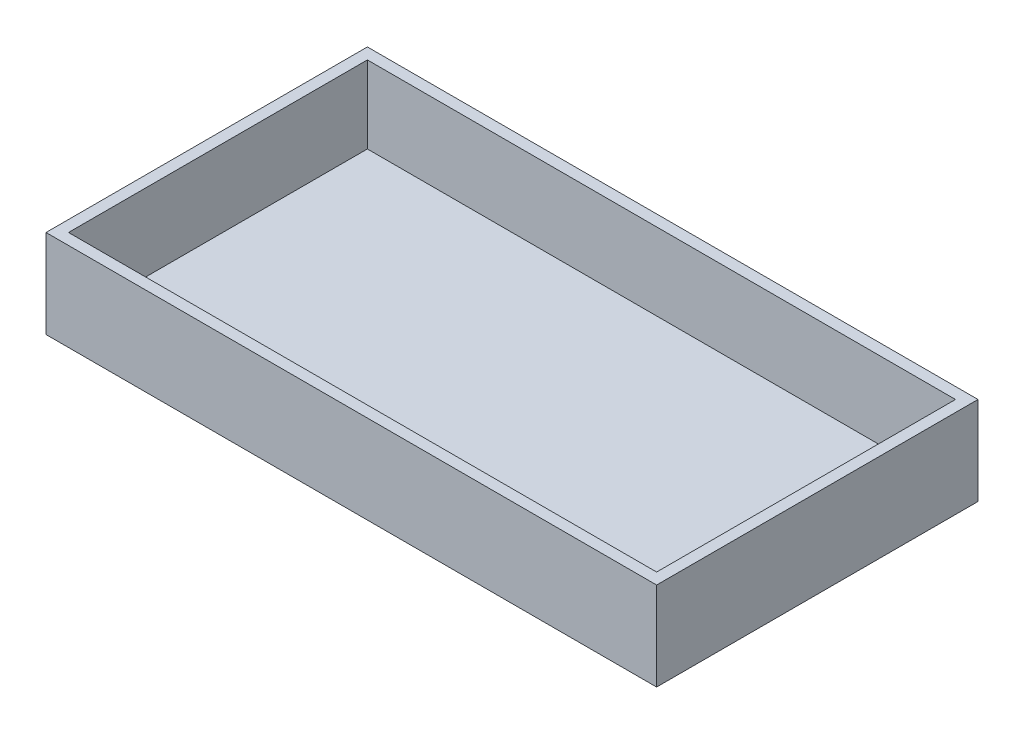
SolidWorks part; units mm, degrees
ref_plane "前视基准面" through (0, 0, 0) normal (0, 0, 1) x (1, 0, 0)
ref_plane "上视基准面" through (0, 0, 0) normal (0, 1, 0) x (1, 0, 0)
ref_plane "右视基准面" through (0, 0, 0) normal (1, 0, 0) x (0, 0, -1)
sketch "草图1" plane through (0, 0, 0) normal (0, 1, 0) x (1, 0, 0)
  line L1 (190, -100) -> (-190, -100)
  line L2 (190, -100) -> (190, 100)
  line L3 (190, 100) -> (-190, 100)
  line L4 (-190, -100) -> (-190, 100)
  line L5 (190, -100) -> (-190, 100) construction
  line L6 (190, 100) -> (-190, -100) construction
  point P0 (0, 0)
  dimension "D1" = 380
  dimension "D2" = 200
extrude "凸台-拉伸1" add sketch "草图1" along normal blind 55
sketch "草图2" plane through (0, 55, 0) normal (0, 1, 0) x (1, 0, 0)
  line L0 (190, 100) -> (-190, 100) construction
  line L1 (183, -93) -> (-183, -93)
  line L2 (183, -93) -> (183, 93)
  line L3 (183, 93) -> (-183, 93)
  line L4 (-183, -93) -> (-183, 93)
  line L5 (183, -93) -> (-183, 93) construction
  line L6 (183, 93) -> (-183, -93) construction
  line L7 (190, -100) -> (190, 100) construction
  point P0 (0, 0)
  dimension "D1" = 7
  dimension "D2" = 7
extrude "切除-拉伸1" cut sketch "草图2" against normal blind 48
